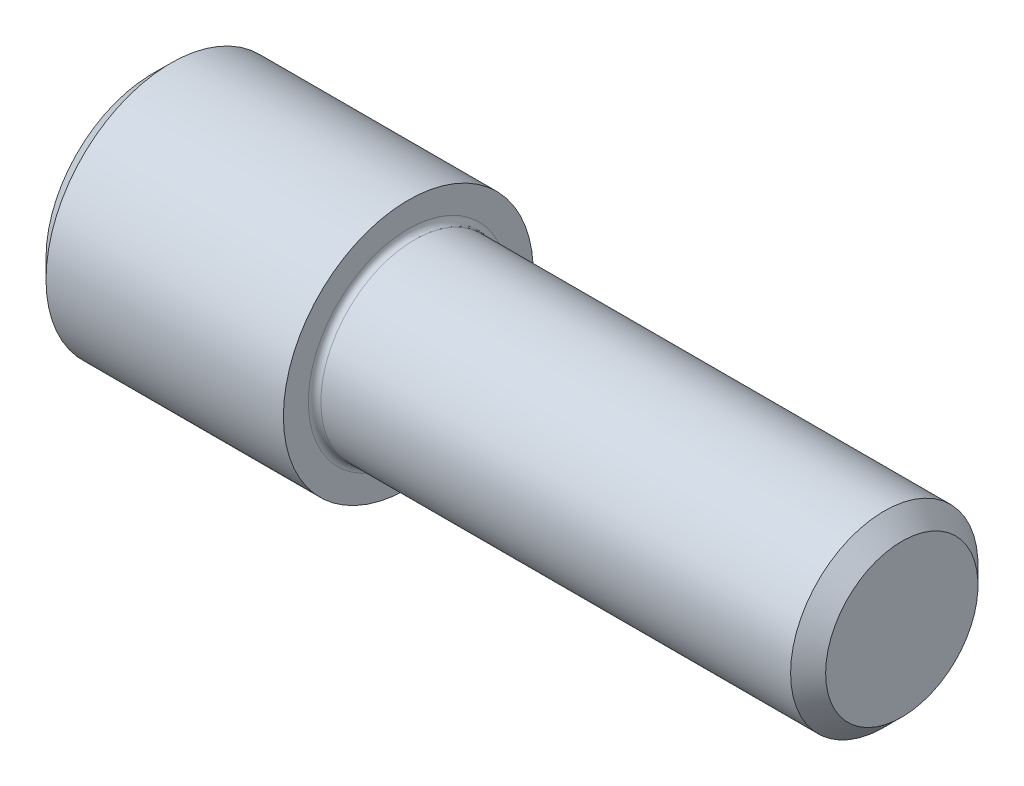
SolidWorks part; units mm, degrees
revolve "Base-Revolve" add sketch "BodySke"
sketch "BodySke" plane through (0, 0, 0) normal (0, 0, 1) x (1, 0, 0)
  line L0 (0, 0) -> (0, 1.7)
  line L1 (0.3, 2) -> (4.1, 2)
  line L2 (4.1, 2) -> (4.1, 1.5)
  line L3 (4.1, 1.5) -> (11.7195, 1.5)
  line L4 (12, 1.2195) -> (12, 0)
  line L5 (12, 0) -> (0, 0)
  line L6 (-31.75, 0) -> (127, 0) construction
  line L7 (0, 1.7) -> (0.3, 2)
  line L8 (12, 1.2195) -> (11.7195, 1.5)
  line L9 (0, -1.7) -> (0.3, -2) construction
  line L10 (12, -1.2195) -> (11.7195, -1.5) construction
  line L11 (4.6, 9.525) -> (4.6, 3.175) construction
  line L12 (7, 9.525) -> (7, 3.175) construction
  line L13 (-38, 9.525) -> (-38, 3.175) construction
  dimension "Diameter" = 3
  dimension "Head_ht" = 4.1
  dimension "Length" = 7.9
  dimension "Body_ch_ang" = 45
  dimension "Head_dia" = 4
  dimension "Head_ch_ang" = 45
  dimension "Minor_dia" = 2.439
  dimension "Advance" = 0.5
  dimension "Thread_nom" = 5
  dimension "Thread_length" = 50
  dimension "Head_ch_ht" = 0.3
cosmetic thread "ThreadCosmetic" [suppressed]
fillet "Fillet1" radius 0.1 1 edges at (4.1, 0, 1.5)
ref_plane "Plane1" through (0, 0, 0) normal (0, 0, 1) x (1, 0, 0)
ref_plane "Plane2" through (0, 0, 0) normal (0, 1, 0) x (1, 0, 0)
ref_plane "Plane3" through (0, 0, 0) normal (1, 0, 0) x (0, 0, -1)
sketch "Sketch2" plane through (0, 0, 0) normal (0, 0, 1) x (1, 0, 0)
  line L0 (0, 1.28) -> (1.3, 1.28)
  line L1 (1.3, 1.28) -> (2.039, 0)
  line L2 (-31.75, 0) -> (127, 0) construction
  line L3 (2.039, 0) -> (0, 0)
  line L4 (0, 0) -> (0, 1.28)
  line L5 (0, 1.7) -> (0, -1.7) construction
  line L6 (0, 0) -> (47.625, 0) construction
  line L7 (4.1, -2) -> (4.1, 2) construction
  dimension "D1" = 1.28
  dimension "D2" = 60
revolve "Hex-PreBroach" cut sketch "Sketch2" angle 360 about L6
sketch "Sketch3" plane through (0, 0, 0) normal (-1, 0, 0) x (0, 0.5, 0.866)
  line L0 (0.739, 1.28) -> (-0.739, 1.28)
  line L1 (-0.739, 1.28) -> (-1.478, 0)
  line L2 (0.739, 1.28) -> (1.478, 0)
  line L3 (0.739, -1.28) -> (1.478, 0)
  line L4 (0.739, -1.28) -> (-0.739, -1.28)
  line L5 (-0.739, -1.28) -> (-1.478, 0)
  dimension "D1" = 1.28
  dimension "D2" = 1.28
  dimension "Hex_size" = 2.56
extrude "Hex" cut sketch "Sketch3" against normal blind 1.3
sketch "Sketch4" plane through (0, 0, 0) normal (-1, 0, 0) x (0, 0, 1)
  line L0 (0, 0) -> (1.4605, 0)
  line L1 (0, 0) -> (6.1484, 3.5498) construction
  line L2 (0, 0) -> (0.7302, 1.2648)
  line L3 (1.2009, 0.3267) -> (1.3933, 0.4378)
  line L4 (0.8834, 0.8767) -> (1.0758, 0.9877)
  arc A0 (1.2009, 0.3267) -> (0.8834, 0.8767) centre (0, 0) ccw
  arc A1 (1.4605, 0) -> (1.3933, 0.4378) centre (0, 0) ccw
  arc A2 (0.7302, 1.2648) -> (1.0758, 0.9877) centre (0, 0) cw
  dimension "D1" = 30
  dimension "D2" = 60
  dimension "Spline_p_dim" = 0.635
  dimension "D3" = 0.3175
extrude "Spline" [suppressed] cut sketch "Sketch4" against normal blind 1.3
pattern_circular "CirPattern1" [suppressed] count 6 every 60
sketch "Sketch5" plane through (0, 0, 0) normal (0, 0, 1) x (1, 0, 0)
  line L0 (-31.75, 0) -> (127, 0) construction
  line L2 (0, 1.7) -> (0, -1.7) construction
  circle A0 centre (1.2, 0) radius 0.475
  dimension "Drilled_hole_dia" = 0.95
  dimension "Drilled_hole_loc" = 1.2
extrude "Hole" [suppressed] cut sketch "Sketch5" against normal through all and the other way through all
pattern_circular "Drilled-4" [suppressed] count 2 every 60
pattern_circular "Drilled-6" [suppressed] count 3 every 60
sketch "ThdSchSke" plane through (0, 0, 0) normal (0, 0, 1) x (1, 0, 0)
  line L0 (7, -1.2195) -> (6.8036, -1.5)
  line L1 (7, -1.2195) -> (7.1964, -1.5)
  line L2 (7.1964, -1.5) -> (7.1964, -1.875)
  line L3 (-3.175, 0) -> (5.1513, 0) construction
  line L5 (7.1964, -1.875) -> (6.8036, -1.875)
  line L6 (6.8036, -1.875) -> (6.8036, -1.5)
  line L7 (0, 1.7) -> (0, -1.7) construction
  dimension "Thread_minor" = 2.439
  dimension "Diameter" = 3
  dimension "Start" = 7
revolve "ThreadSchematic" [suppressed] cut sketch "ThdSchSke" angle 360 about L3
pattern_linear "ThdSchPat" [suppressed]
equation "\"D2@Sketch3\" = \"Hex_size@Sketch3\" / 2"
equation "\"D1@Sketch3\" = \"Hex_size@Sketch3\" / 2"
equation "\"D1@Sketch2\" = \"Hex_size@Sketch3\" / 2"
equation "\"D3@Sketch4\" = \"Spline_p_dim@Sketch4\" / 2"
equation "\"Thread_minor@ThreadCosmetic\"  =  \"Minor_dia@BodySke\""
equation "\"D2@CirPattern1\" = 360 / \"Num_teeth@CirPattern1\""
equation "\"Wall_thickness@Sketch2\" = \"Head_ht@BodySke\" - \"Key_eng@Hex\""
equation "\"Thread_length@ThreadCosmetic\" = ((sgn( (\"Length@BodySke\" - \"Advance@BodySke\" ) - \"Thread_nom@BodySke\" )-1)*( (\"Length@BodySke\" - \"Advance@BodySke\" ) - \"Thread_nom@BodySke\" ))/-2+ \"Thread_nom@BodySke\""
equation "\"Thread_minor@ThdSchSke\" = \"Minor_dia@BodySke\""
equation "\"Diameter@ThdSchSke\" = \"Diameter@BodySke\""
equation "\"Overcut@ThdSchSke\" = \"Diameter@BodySke\" * 1.25"
equation "\"Start@ThdSchSke\" = \"Head_ht@BodySke\" + \"Length@BodySke\" - \"Thread_length@ThreadCosmetic\"  '---Non-countersunk---"
equation "\"Num_threads@ThdSchPat\" = int( \"Thread_length@ThreadCosmetic\" / \"Advance@BodySke\" + 0.999 )  + 1"
equation "\"Advance@ThdSchPat\" = \"Thread_length@ThreadCosmetic\" /  (\"Num_threads@ThdSchPat\" - 1) 'relax it"
equation "\"Num_threads@ThdSchPat\" = \"Num_threads@ThdSchPat\" - sgn( \"Num_threads@ThdSchPat\" - 1) '---chamfered tips only---"
